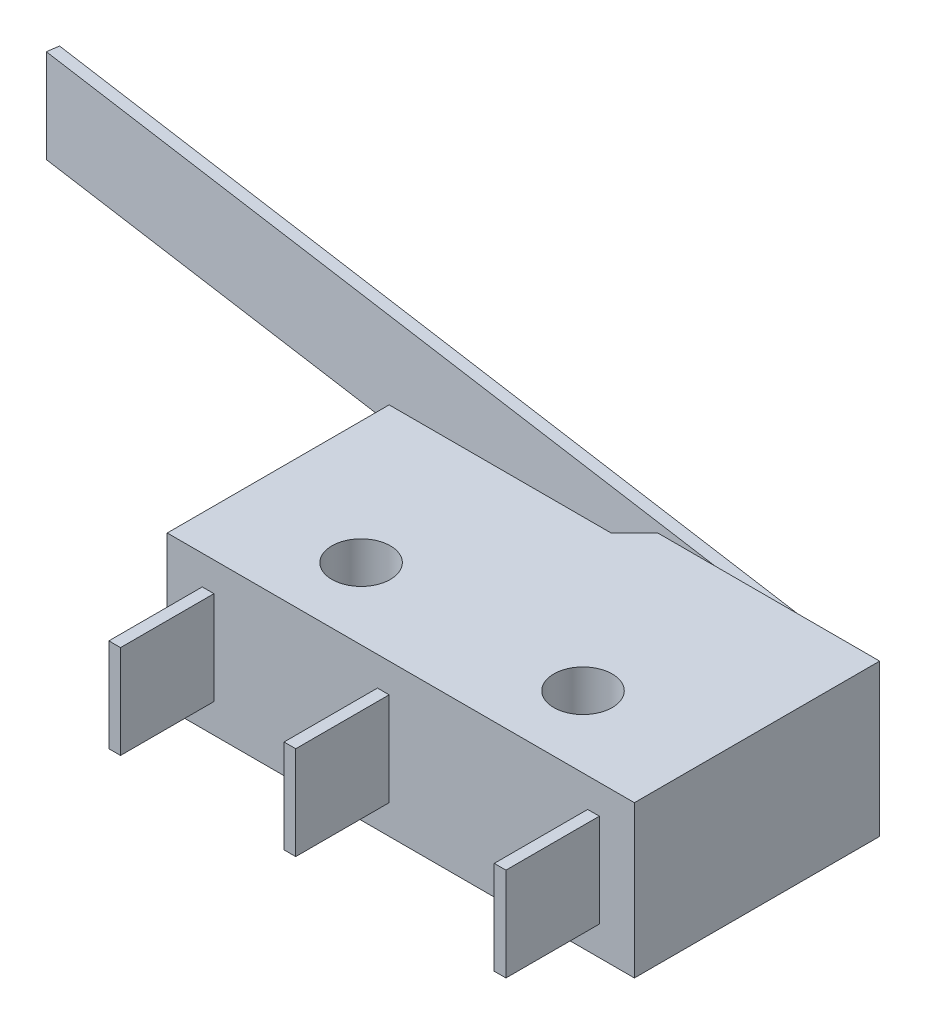
SolidWorks part; units mm, degrees
ref_plane "Front Plane" through (0, 0, 0) normal (0, 0, 1) x (1, 0, 0)
ref_plane "Top Plane" through (0, 0, 0) normal (0, 1, 0) x (1, 0, 0)
ref_plane "Right Plane" through (0, 0, 0) normal (1, 0, 0) x (0, 0, -1)
sketch "Sketch1" plane through (0, 0, 0) normal (0, 1, 0) x (1, 0, 0)
  line L0 (0, 9.5) -> (9.5, 9.5)
  line L1 (0, 0) -> (20, 0)
  line L2 (0, 0) -> (0, 9.5)
  line L3 (10.5, 10.5) -> (20, 10.5)
  line L4 (20, 0) -> (20, 10.5)
  line L5 (9.5, 9.5) -> (10.5, 10.5)
  dimension "D1" = 20
  dimension "D2" = 10.5
  dimension "D3" = 9.5
  dimension "D4" = 9.5
  dimension "D5" = 9.5
extrude "Boss-Extrude1" add sketch "Sketch1" along normal mid plane 6.5
sketch "Sketch2" plane through (0, 0, 0) normal (0, 1, 0) x (1, 0, 0)
  line L0 (17, 10.5) -> (17, 11.5)
  line L1 (20, 10.5) -> (10.5, 10.5) construction
  line L2 (17, 11.5) -> (-21.6102, 17)
  line L3 (-21.6102, 17) -> (-21.6807, 16.505)
  line L4 (-21.6807, 16.505) -> (16.5, 11.0662)
  line L5 (16.5, 11.0662) -> (16.5, 10.5)
  line L6 (16.5, 10.5) -> (17, 10.5)
  line L7 (20, 0) -> (20, 10.5) construction
  line L8 (0, 0) -> (20, 0) construction
  line L9 (0, 9.5) -> (0, 0) construction
  line L10 (18.5, 0) -> (18, 0)
  line L11 (18.5, 0) -> (18.5, -4)
  line L12 (18.5, -4) -> (18, -4)
  line L13 (18, 0) -> (18, -4)
  line L14 (9.5, 0) -> (9, 0)
  line L15 (9.5, 0) -> (9.5, -4)
  line L16 (9.5, -4) -> (9, -4)
  line L17 (9, 0) -> (9, -4)
  line L18 (2, 0) -> (1.5, 0)
  line L19 (2, 0) -> (2, -4)
  line L20 (2, -4) -> (1.5, -4)
  line L21 (1.5, 0) -> (1.5, -4)
  dimension "D1" = 39
  dimension "D2" = 0.5
  dimension "D3" = 0.5
  dimension "D4" = 3
  dimension "D5" = 11.5
  dimension "D6" = 17
  dimension "D7" = 0.5
  dimension "D8" = 4
  dimension "D9" = 2
  dimension "D10" = 2
  dimension "D11" = 9.5
extrude "Boss-Extrude2" add sketch "Sketch2" along normal mid plane 4
sketch "Sketch3" plane through (0, 3.25, 0) normal (0, 1, 0) x (1, 0, 0)
  line L0 (20, 0) -> (20, 10.5) construction
  line L1 (0, 0) -> (20, 0) construction
  circle A0 centre (5.25, 3.05) radius 1.25
  circle A1 centre (14.75, 3.05) radius 1.25
  dimension "D1" = 2.5
  dimension "D2" = 9.5
  dimension "D3" = 5.25
  dimension "D4" = 3.05
extrude "Cut-Extrude1" cut sketch "Sketch3" against normal blind 14
sketch "Sketch4" plane through (0, 0, 0) normal (0, 1, 0) x (1, 0, 0)
  line L0 (17, 11.5) -> (-21.6102, 17) construction
  line L1 (-21.6102, 17) -> (-21.6807, 16.505) construction
  line L2 (-22, 11.5) -> (17, 11.5)
  line L3 (17, 11.5) -> (0.1779, 17.3344) construction
  line L4 (-0.8052, 17.5) -> (17, 17.5)
  line L5 (17, 17.5) -> (17, 11.5)
  line L6 (0.1779, 17.3344) -> (-19.8468, 24.2795) construction
  line L7 (-0.8052, 14.5) -> (-0.8052, 59.3637) construction
  arc A0 (-21.6102, 17) -> (-22, 11.5) centre (17, 11.5) ccw
  circle A1 centre (-0.8052, 14.5) radius 3
  circle A2 centre (-21.0732, 19.9515) radius 3
  arc A3 (-20.311, 22.8531) -> (-19.8468, 24.2795) centre (17, 11.5) cw
  circle A4 centre (-0.8052, 47.631) radius 30.131
  dimension "D1" = 6
  dimension "D3" = 60.2621
  dimension "D2" = 1.5
